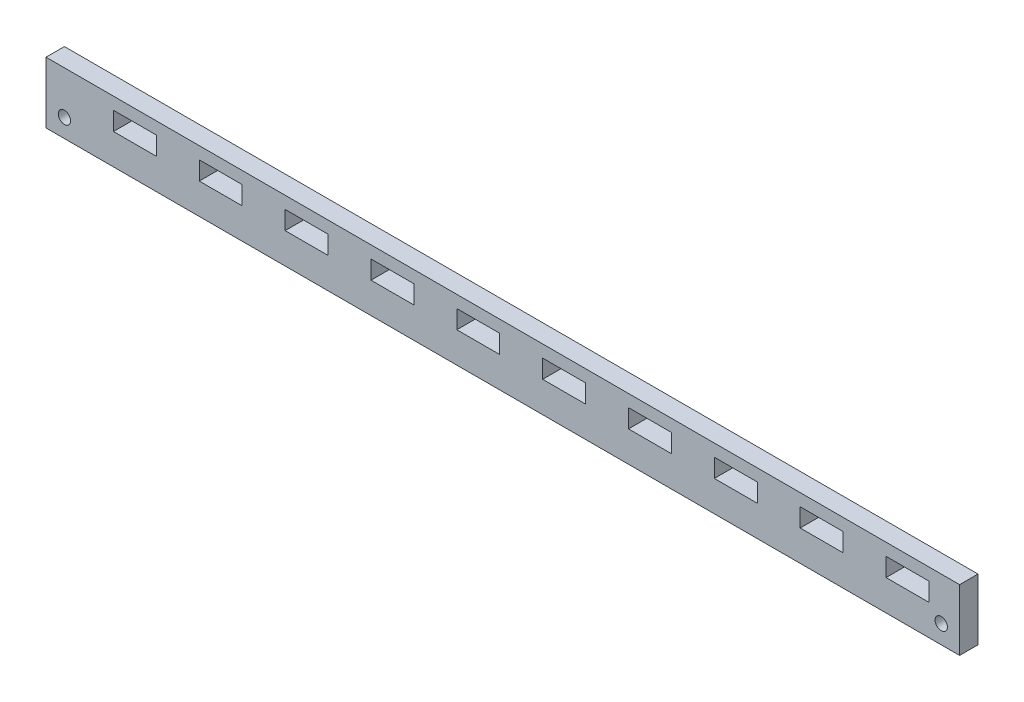
SolidWorks part; units mm, degrees
ref_plane "Plan de face" through (0, 0, 0) normal (0, 0, 1) x (1, 0, 0)
ref_plane "Plan de dessus" through (0, 0, 0) normal (0, 1, 0) x (1, 0, 0)
ref_plane "Plan de droite" through (0, 0, 0) normal (1, 0, 0) x (0, 0, -1)
sketch "Esquisse1" plane through (0, 0, 0) normal (0, 0, 1) x (1, 0, 0)
  line L1 (0, 0) -> (149, 0)
  line L2 (0, 0) -> (0, 10)
  line L3 (0, 10) -> (149, 10)
  line L4 (149, 0) -> (149, 10)
  dimension "D1" = 10
  dimension "D2" = 149
extrude "Boss.-Extru.1" add sketch "Esquisse1" along normal blind 3
sketch "Esquisse2" plane through (0, 0, 0) normal (0, 0, -1) x (-1, 0, 0)
  line L0 (0, 0) -> (-149, 0) construction
  line L1 (-149, 10) -> (0, 10) construction
  line L2 (-144, 8) -> (-137, 8)
  line L3 (-144, 8) -> (-144, 5)
  line L4 (-144, 5) -> (-137, 5)
  line L5 (-149, 0) -> (-149, 10) construction
  line L6 (0, 10) -> (0, 0) construction
  line L8 (-137, 8) -> (-137, 5)
  line L9 (-130, 8) -> (-123, 8)
  line L10 (-130, 8) -> (-130, 5)
  line L11 (-130, 5) -> (-123, 5)
  line L12 (-123, 8) -> (-123, 5)
  line L13 (-116, 8) -> (-109, 8)
  line L14 (-116, 8) -> (-116, 5)
  line L15 (-116, 5) -> (-109, 5)
  line L16 (-109, 8) -> (-109, 5)
  line L17 (-102, 8) -> (-95, 8)
  line L18 (-102, 8) -> (-102, 5)
  line L19 (-102, 5) -> (-95, 5)
  line L20 (-95, 8) -> (-95, 5)
  line L21 (-88, 8) -> (-81, 8)
  line L22 (-88, 8) -> (-88, 5)
  line L23 (-88, 5) -> (-81, 5)
  line L24 (-81, 8) -> (-81, 5)
  line L25 (-74, 8) -> (-67, 8)
  line L26 (-74, 8) -> (-74, 5)
  line L27 (-74, 5) -> (-67, 5)
  line L28 (-67, 8) -> (-67, 5)
  line L29 (-60, 8) -> (-53, 8)
  line L30 (-60, 8) -> (-60, 5)
  line L31 (-60, 5) -> (-53, 5)
  line L32 (-53, 8) -> (-53, 5)
  line L33 (-46, 8) -> (-39, 8)
  line L34 (-46, 8) -> (-46, 5)
  line L35 (-46, 5) -> (-39, 5)
  line L36 (-39, 8) -> (-39, 5)
  line L37 (-32, 8) -> (-25, 8)
  line L38 (-32, 8) -> (-32, 5)
  line L39 (-32, 5) -> (-25, 5)
  line L40 (-25, 8) -> (-25, 5)
  line L41 (-18, 8) -> (-11, 8)
  line L42 (-18, 8) -> (-18, 5)
  line L43 (-18, 5) -> (-11, 5)
  line L44 (-11, 8) -> (-11, 5)
  line L61 (-4, 8) -> (3, 8) [skipped]
  line L62 (-4, 8) -> (-4, 5) [skipped]
  line L63 (-4, 5) -> (3, 5) [skipped]
  line L64 (3, 8) -> (3, 5) [skipped]
  line L65 (10, 8) -> (17, 8) [skipped]
  line L66 (10, 8) -> (10, 5) [skipped]
  line L67 (10, 5) -> (17, 5) [skipped]
  line L68 (17, 8) -> (17, 5) [skipped]
  line L69 (24, 8) -> (31, 8) [skipped]
  line L70 (24, 8) -> (24, 5) [skipped]
  line L71 (24, 5) -> (31, 5) [skipped]
  line L72 (31, 8) -> (31, 5) [skipped]
  line L73 (38, 8) -> (45, 8) [skipped]
  line L74 (38, 8) -> (38, 5) [skipped]
  line L75 (38, 5) -> (45, 5) [skipped]
  line L76 (45, 8) -> (45, 5) [skipped]
  circle A0 centre (-3, 3) radius 1.005
  circle A1 centre (-146, 3) radius 1.005
  dimension "D1" = 2.01
  dimension "D2" = 2.01
  dimension "D3" = 3
  dimension "D4" = 3
  dimension "D5" = 7
  dimension "D6" = 3
  dimension "D9" = 3
  dimension "D13" = 3
  dimension "D7" = 5
  dimension "D8" = 2
  dimension "D10" = 14
  dimension "D11" = 2
  dimension "D12" = 7
extrude "Enlèv. mat.-Extru.1" cut sketch "Esquisse2" against normal through all
